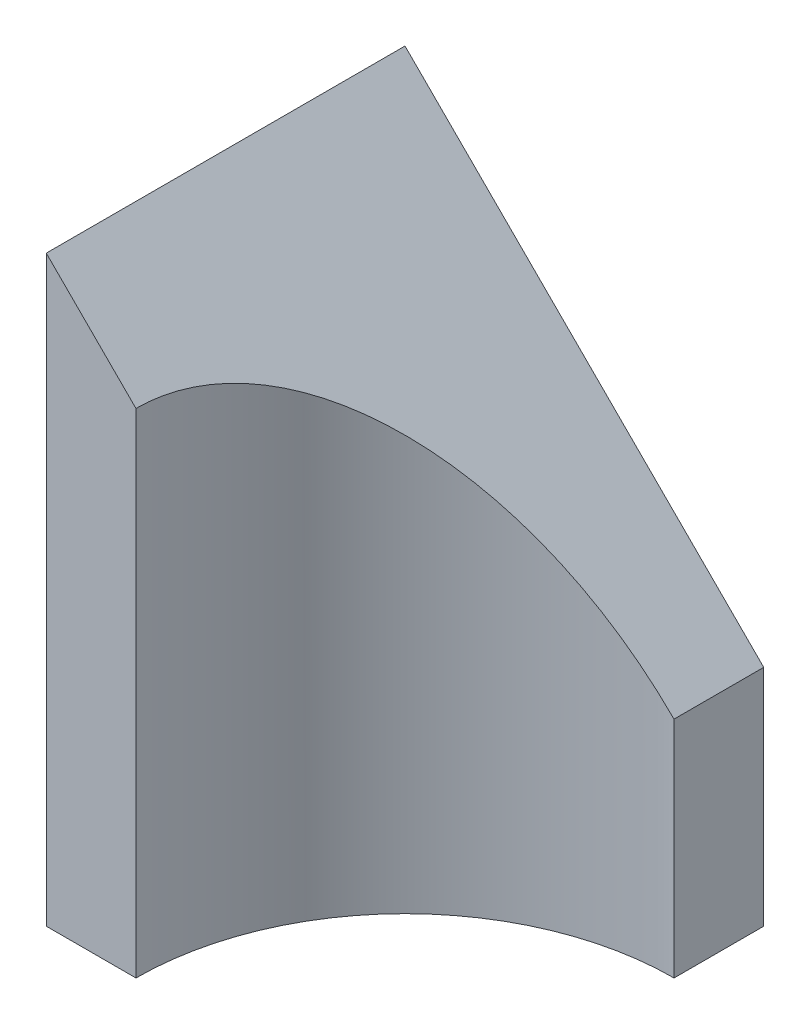
SolidWorks part; units mm, degrees
ref_plane "Front Plane" through (0, 0, 0) normal (0, 0, 1) x (1, 0, 0)
ref_plane "Top Plane" through (0, 0, 0) normal (0, 1, 0) x (1, 0, 0)
ref_plane "Right Plane" through (0, 0, 0) normal (1, 0, 0) x (0, 0, -1)
sketch "Sketch1" plane through (0, 0, 0) normal (0, 1, 0) x (1, 0, 0)
  line L0 (0, 0) -> (0, -50.8)
  line L1 (0, -50.8) -> (12.7, -50.8)
  line L2 (50.8, -12.7) -> (50.8, 0)
  line L3 (50.8, 0) -> (0, 0)
  arc A0 (50.8, -12.7) -> (12.7, -50.8) centre (50.8, -50.8) ccw
  dimension "D2" = 38.1
  dimension "D1" = 50.8
extrude "Boss-Extrude1" add sketch "Sketch1" along normal blind 82.55
sketch "Sketch2" plane through (0, 0, 0) normal (0, 0, 1) x (1, 0, 0)
  line L0 (0, 82.55) -> (50.8, 31.75)
  line L1 (50.8, 82.55) -> (50.8, 0) construction
  line L2 (0, 82.55) -> (0, 0) construction
  dimension "D1" = 45
extrude "Cut-Extrude1" cut sketch "Sketch2" against normal through all and the other way through all
